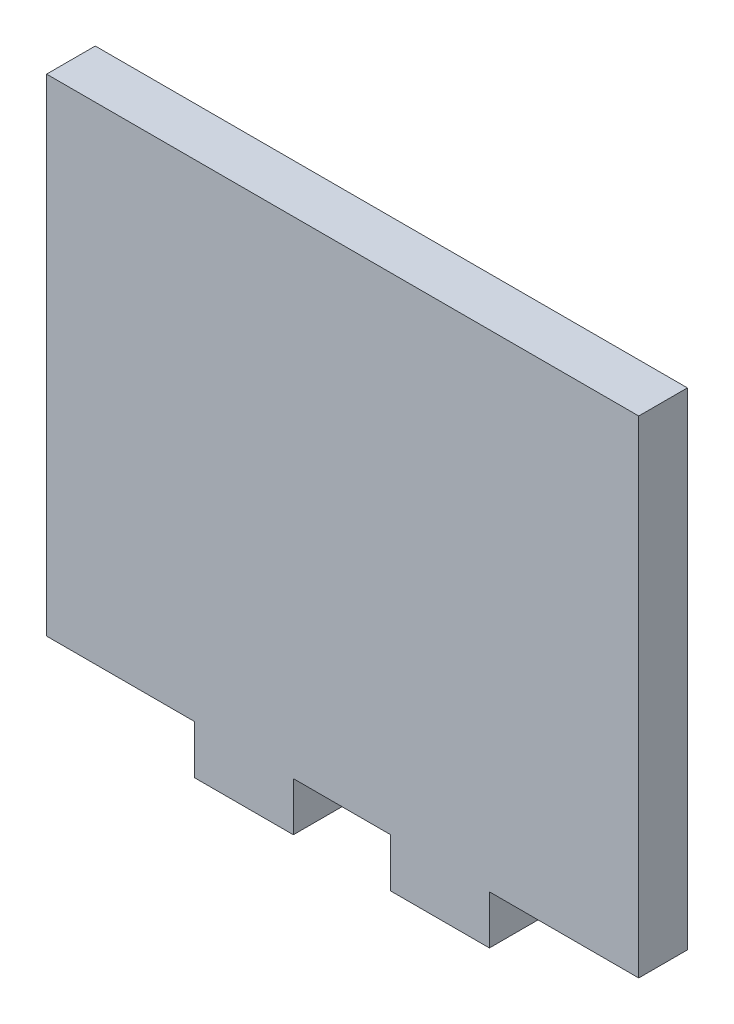
SolidWorks part; units mm, degrees
ref_plane "Plan de face" through (0, 0, 0) normal (0, 0, 1) x (1, 0, 0)
ref_plane "Plan de dessus" through (0, 0, 0) normal (0, 1, 0) x (1, 0, 0)
ref_plane "Plan de droite" through (0, 0, 0) normal (1, 0, 0) x (0, 0, -1)
sketch "Esquisse1" plane through (0, 0, 0) normal (0, 0, 1) x (1, 0, 0)
  line L0 (-13.0644, 0) -> (2.1456, 0)
  line L1 (-13.0644, 50) -> (47.7656, 50)
  line L5 (2.1456, 0) -> (2.1456, -5)
  line L6 (2.1456, -5) -> (12.2856, -5)
  line L7 (12.2856, -5) -> (12.2856, 0)
  line L8 (12.2856, 0) -> (22.2856, 0)
  line L9 (22.2856, 0) -> (22.2856, -5)
  line L10 (22.2856, -5) -> (32.4256, -5)
  line L11 (32.4256, -5) -> (32.4256, 0)
  line L12 (32.4256, 0) -> (47.7656, 0)
  line L13 (47.7656, 50) -> (47.7656, 0)
  line L14 (-13.0644, 50) -> (-13.0644, 0)
  point P6 (32.4256, -2.5)
  dimension "D1" = 5
  dimension "D2" = 5
  dimension "D3" = 10.14
  dimension "D4" = 10.14
  dimension "D5" = 15.34
  dimension "D6" = 10
  dimension "D7" = 15.21
  dimension "D8" = 50
extrude "Boss.-Extru.1" add sketch "Esquisse1" along normal blind 5
